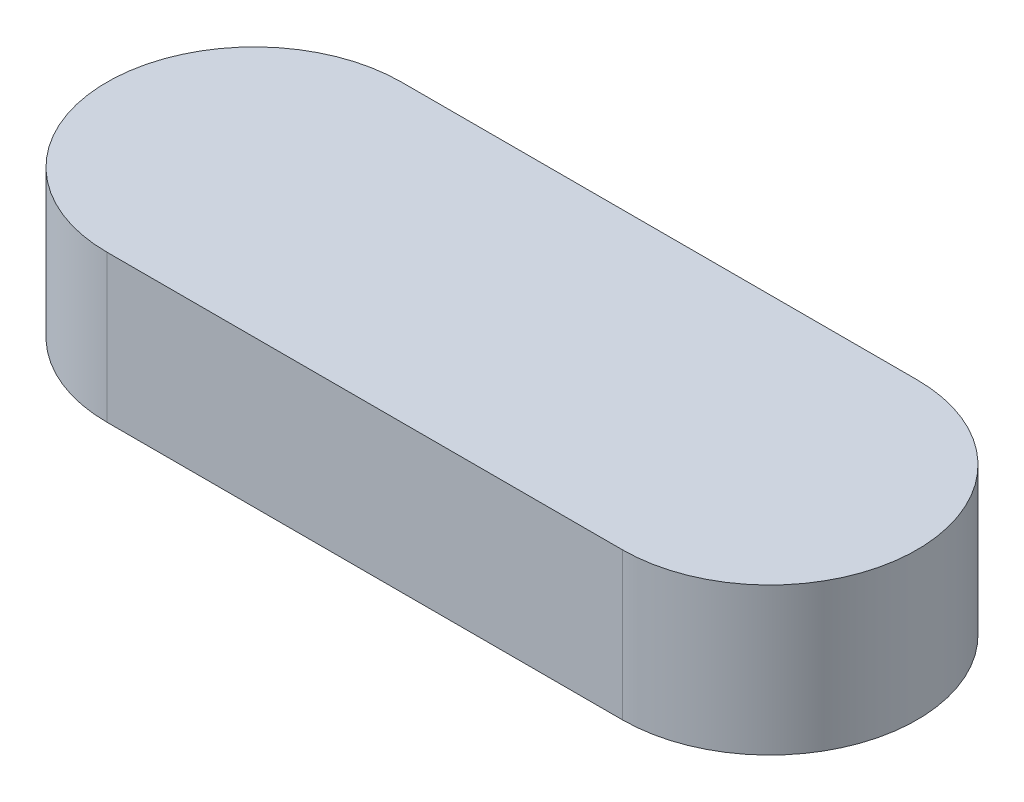
SolidWorks part; units mm, degrees
ref_plane "Alzado" through (0, 0, 0) normal (0, 0, 1) x (1, 0, 0)
ref_plane "Planta" through (0, 0, 0) normal (0, 1, 0) x (1, 0, 0)
ref_plane "Vista lateral" through (0, 0, 0) normal (1, 0, 0) x (0, 0, -1)
sketch "Croquis1" plane through (0, 0, 0) normal (0, 1, 0) x (1, 0, 0)
  line L0 (0, 0) -> (-350, 0) construction
  line L1 (0, -100) -> (-350, -100)
  line L2 (0, 100) -> (-350, 100)
  arc A0 (0, -100) -> (0, 100) centre (0, 0) ccw
  arc A1 (-350, 100) -> (-350, -100) centre (-350, 0) ccw
  point P3 (-175, 0)
  dimension "D1" = 350
  dimension "D2" = 200
extrude "Saliente-Extruir1" add sketch "Croquis1" along normal blind 100
